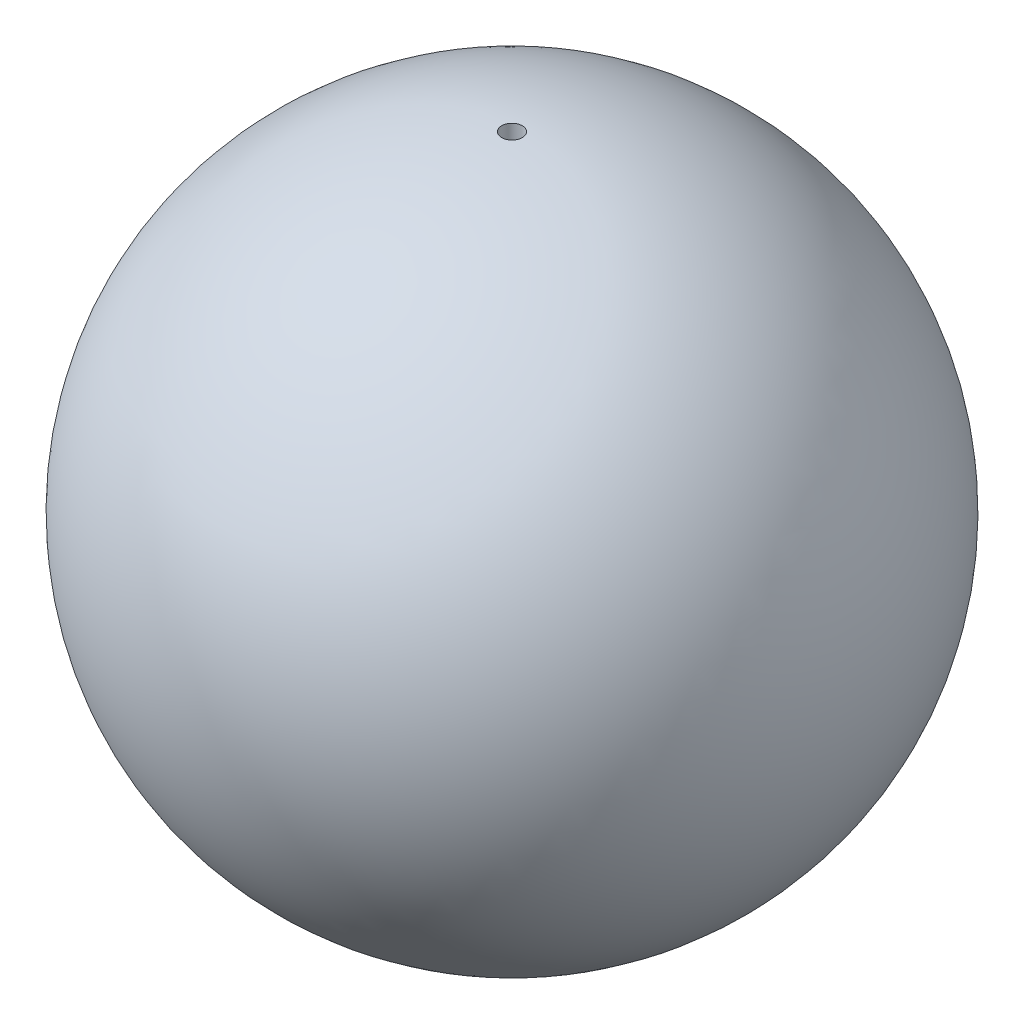
SolidWorks part; units mm, degrees
ref_plane "Front Plane" through (0, 0, 0) normal (0, 0, 1) x (1, 0, 0)
ref_plane "Top Plane" through (0, 0, 0) normal (0, 1, 0) x (1, 0, 0)
ref_plane "Right Plane" through (0, 0, 0) normal (1, 0, 0) x (0, 0, -1)
sketch "Sketch1" plane through (0, 0, 0) normal (0, 0, 1) x (1, 0, 0)
  line L0 (0, 203.2) -> (0, -203.2) construction
  line L1 (0, 203.2) -> (0, -203.2)
  arc A0 (0, 203.2) -> (0, -203.2) centre (0, 0) ccw
  dimension "D1" = 406.4
revolve "Revolve2" add sketch "Sketch1" angle 360 about L0
sketch "Sketch2" plane through (0, 0, 0) normal (0, 1, 0) x (1, 0, 0)
  circle A0 centre (0, 0) radius 6.35
  dimension "D1" = 12.7
extrude "Cut-Extrude1" cut sketch "Sketch2" against normal through all both and the other way through all
